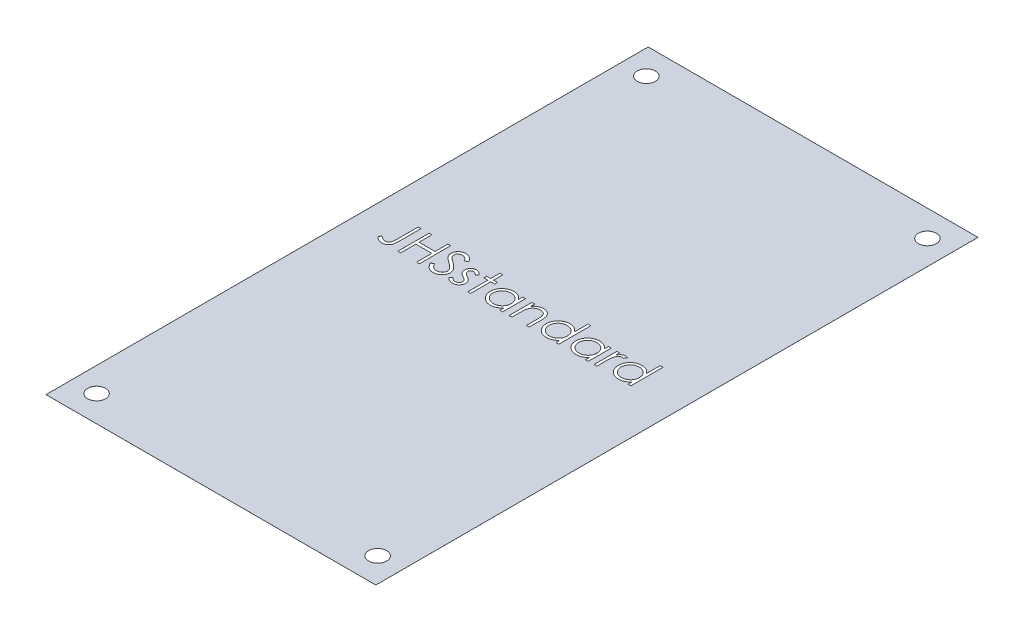
SolidWorks part; units mm, degrees
ref_plane "Front Plane" through (0, 0, 0) normal (0, 0, 1) x (1, 0, 0)
ref_plane "Top Plane" through (0, 0, 0) normal (0, 1, 0) x (1, 0, 0)
ref_plane "Right Plane" through (0, 0, 0) normal (1, 0, 0) x (0, 0, -1)
sketch "Sketch2" plane through (0, 0, 0) normal (0, 1, 0) x (1, 0, 0)
  line L1 (-33.528, -61.214) -> (33.528, -61.214)
  line L2 (-33.528, -61.214) -> (-33.528, 61.214)
  line L3 (-33.528, 61.214) -> (33.528, 61.214)
  line L4 (33.528, -61.214) -> (33.528, 61.214)
  line L5 (-33.528, -61.214) -> (33.528, 61.214) construction
  line L6 (-33.528, 61.214) -> (33.528, -61.214) construction
  point P0 (0, 0)
  dimension "D1" = 122.428
  dimension "D2" = 67.056
extrude "Boss-Extrude1" add sketch "Sketch2" along normal blind 0.0025
sketch "Sketch3" plane through (0, 0.0025, 0) normal (0, 1, 0) x (1, 0, 0)
  line L1 (-28.575, -55.88) -> (28.575, -55.88)
  line L2 (-28.575, -55.88) -> (-28.575, 55.88)
  line L3 (-28.575, 55.88) -> (28.575, 55.88)
  line L4 (28.575, -55.88) -> (28.575, 55.88)
  line L5 (-28.575, -55.88) -> (28.575, 55.88) construction
  line L6 (-28.575, 55.88) -> (28.575, -55.88) construction
  circle A0 centre (-28.575, 55.88) radius 1.8288
  circle A7 centre (28.575, 55.88) radius 1.8288
  circle A8 centre (28.575, -55.88) radius 1.8288
  circle A9 centre (-28.575, -55.88) radius 1.8288
  point P0 (0, 0)
  dimension "D3" = 3.6576
  dimension "D1" = 111.76
  dimension "D2" = 57.15
  dimension "D4" = 2
  dimension "D5" = 2
extrude "Cut-Extrude1" cut sketch "Sketch3" against normal through all contours A9 | A8 | A7 | A0
sketch "Sketch5" plane through (0, 0.0025, 0) normal (0, 1, 0) x (1, 0, 0)
  text T0 "JHSstandard" font "Century Gothic" height 6.35
  point P1 (-23.0976, -2.5229)
extrude "Cut-Extrude2" cut sketch "Sketch5" against normal blind 2.54
